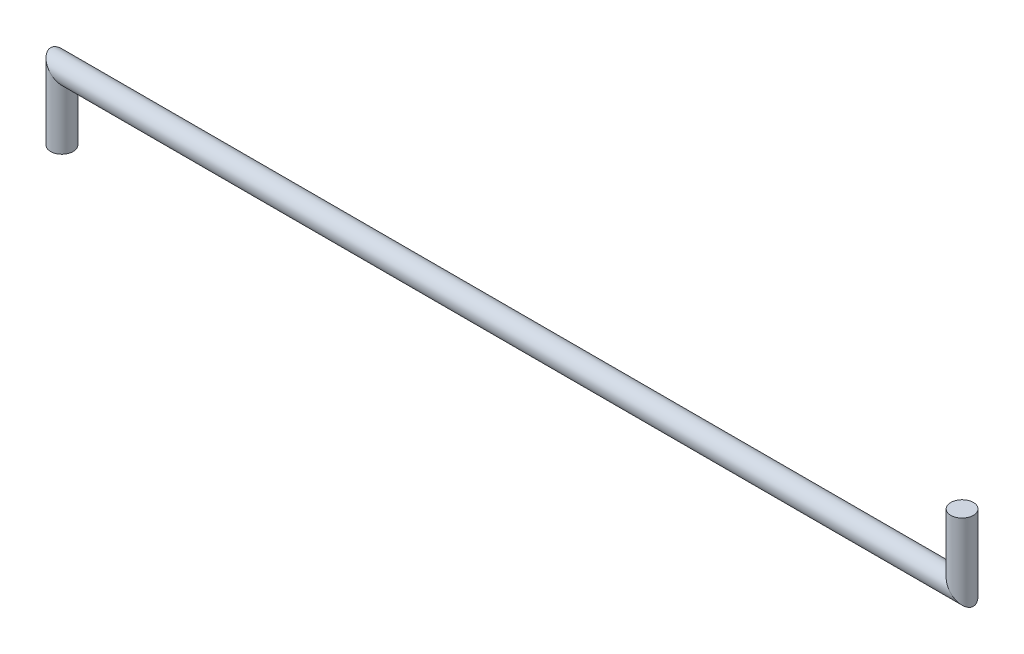
SolidWorks part; units mm, degrees
ref_plane "Alzado" through (0, 0, 0) normal (0, 0, 1) x (1, 0, 0)
ref_plane "Planta" through (0, 0, 0) normal (0, 1, 0) x (1, 0, 0)
ref_plane "Vista lateral" through (0, 0, 0) normal (1, 0, 0) x (0, 0, -1)
sketch "Croquis1" plane through (0, 0, 0) normal (0, 0, 1) x (1, 0, 0)
  line L0 (-77.0818, 4.9014) -> (-37.0818, 4.9014)
  line L1 (-77.0818, 4.9014) -> (-77.0818, 1.9014)
  line L2 (-37.0818, 4.9014) -> (-37.0818, 7.9014)
  dimension "D1" = 40
ref_plane "Plano1" through (0, 7.9014, 0) normal (0, 1, 0) x (1, 0, 0)
sketch "Croquis2" plane through (0, 7.9014, 0) normal (0, 1, 0) x (1, 0, 0)
  line L0 (-77.0818, 0) -> (-37.0818, 0) construction
  circle A0 centre (-37.0818, 0) radius 0.5
sweep "Barrer2" add profiles "Croquis2" path "Croquis1"
